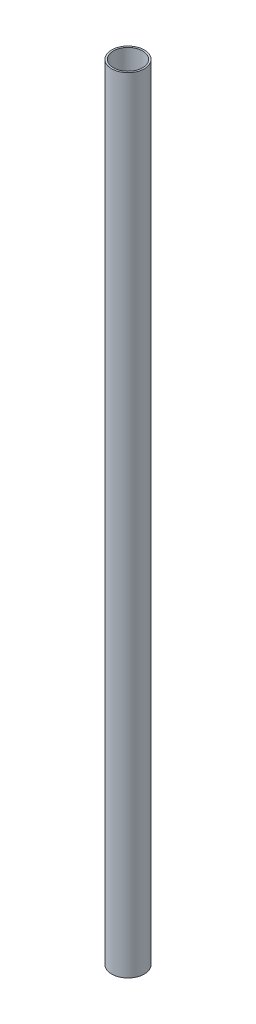
SolidWorks part; units mm, degrees
ref_plane "Front Plane" through (0, 0, 0) normal (0, 0, 1) x (1, 0, 0)
ref_plane "Top Plane" through (0, 0, 0) normal (0, 1, 0) x (1, 0, 0)
ref_plane "Right Plane" through (0, 0, 0) normal (1, 0, 0) x (0, 0, -1)
sketch "Sketch1" plane through (0, 0, 0) normal (0, 1, 0) x (1, 0, 0)
  circle A0 centre (0, 0) radius 57.15
  circle A1 centre (0, 0) radius 51.1302
  dimension "D1" = 102.2604
  dimension "D2" = 114.3
extrude "Boss-Extrude1" add sketch "Sketch1" along normal blind 2743.2
